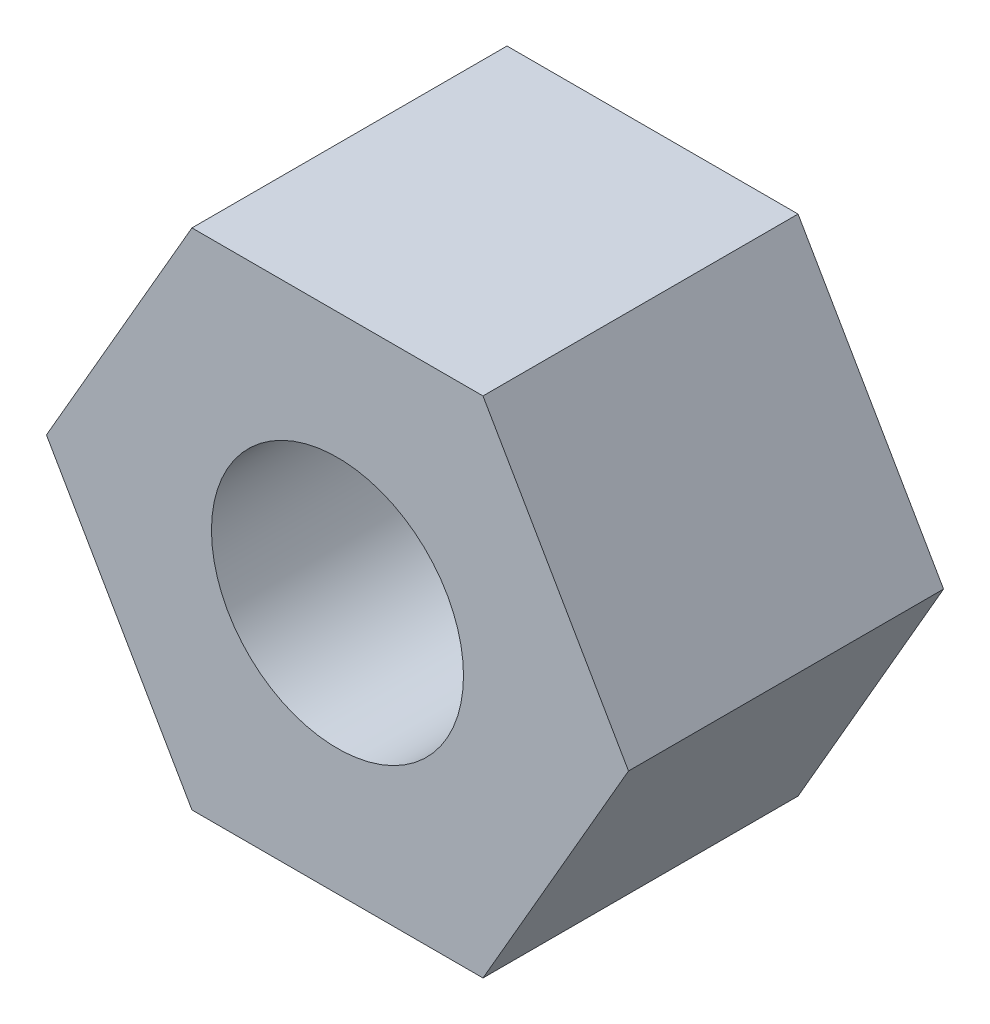
SolidWorks part; units mm, degrees
ref_plane "前视基准面" through (0, 0, 0) normal (0, 0, 1) x (1, 0, 0)
ref_plane "上视基准面" through (0, 0, 0) normal (0, 1, 0) x (1, 0, 0)
ref_plane "右视基准面" through (0, 0, 0) normal (1, 0, 0) x (0, 0, -1)
sketch "Sketch1" plane through (0, 0, 0) normal (0, 0, 1) x (1, 0, 0)
  line L1 (4.6188, 0) -> (2.3094, 4)
  line L2 (2.3094, 4) -> (-2.3094, 4)
  line L3 (-2.3094, 4) -> (-4.6188, 0)
  line L4 (-4.6188, 0) -> (-2.3094, -4)
  line L5 (-2.3094, -4) -> (2.3094, -4)
  line L6 (2.3094, -4) -> (4.6188, 0)
  circle A0 centre (0, 0) radius 4 construction
extrude "Boss-Extrude1" add sketch "Sketch1" along normal blind 5
sketch "Sketch2" plane through (0, 0, 5) normal (0, 0, 1) x (1, 0, 0)
  circle A0 centre (0, 0) radius 2
extrude "Cut-Extrude1" cut sketch "Sketch2" against normal blind 5
